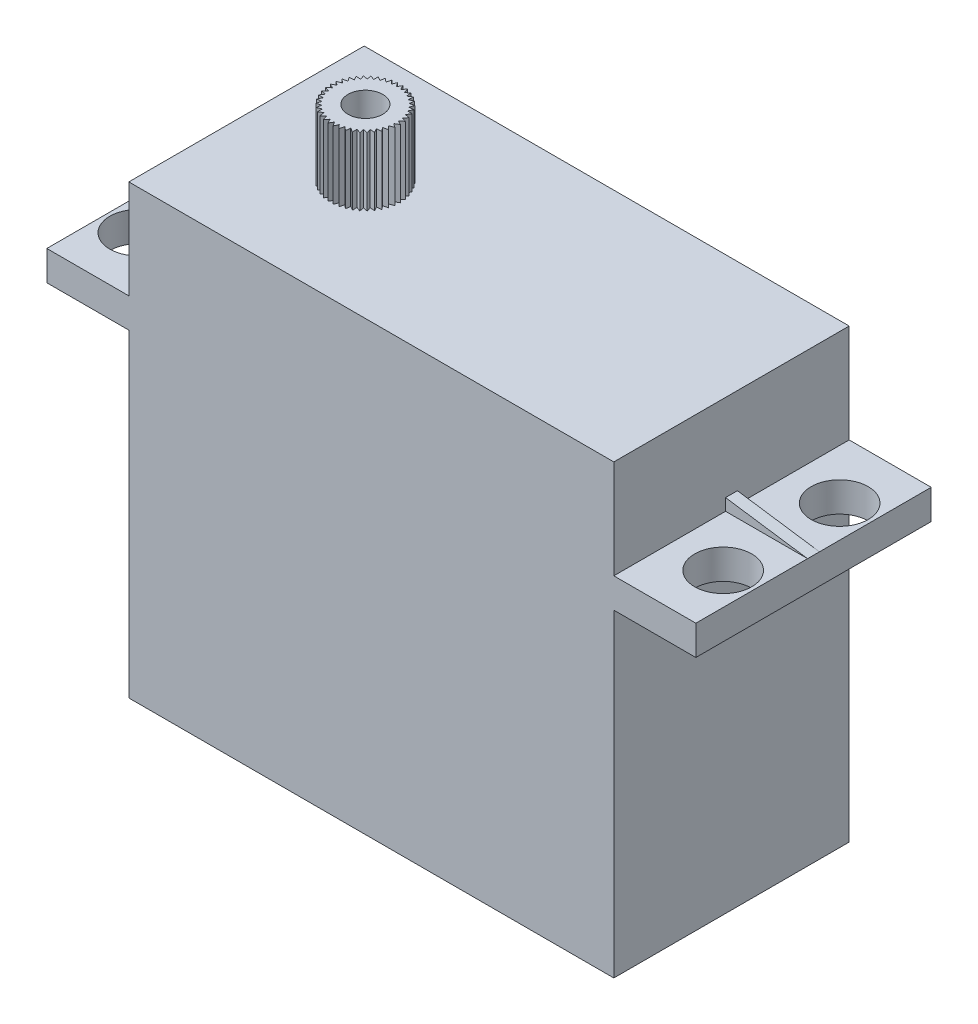
SolidWorks part; units mm, degrees
ref_plane "Front Plane" through (0, 0, 0) normal (0, 0, 1) x (1, 0, 0)
ref_plane "Top Plane" through (0, 0, 0) normal (0, 1, 0) x (1, 0, 0)
ref_plane "Right Plane" through (0, 0, 0) normal (1, 0, 0) x (0, 0, -1)
sketch "Sketch1" plane through (0, 0, 0) normal (0, 1, 0) x (1, 0, 0)
  line L1 (-27.3, -9.9) -> (27.3, -9.9)
  line L2 (-27.3, -9.9) -> (-27.3, 9.9)
  line L3 (-27.3, 9.9) -> (27.3, 9.9)
  line L4 (27.3, -9.9) -> (27.3, 9.9)
  line L5 (-27.3, -9.9) -> (27.3, 9.9) construction
  line L6 (-27.3, 9.9) -> (27.3, -9.9) construction
  point P0 (0, 0)
  dimension "D1" = 54.6
  dimension "D2" = 19.8
extrude "Full Block" add sketch "Sketch1" along normal blind 37.6
sketch "Sketch2" plane through (0, 0, 9.9) normal (0, 0, 1) x (1, 0, 0)
  line L0 (0, 0) -> (0, 37.6) construction
  line L1 (-27.3, 0) -> (27.3, 0) construction
  line L2 (-27.3, 37.6) -> (27.3, 37.6) construction
  line L4 (-20.4, 0) -> (-20.4, 37.6)
  line L5 (-20.4, 26.8) -> (-27.3, 26.8)
  line L6 (-27.3, 37.6) -> (-27.3, 0) construction
  line L7 (-27.3, 29.3) -> (-20.4, 29.3)
  line L8 (27.3, 29.3) -> (20.4, 29.3)
  line L9 (20.4, 26.8) -> (27.3, 26.8)
  line L10 (20.4, 0) -> (20.4, 37.6)
  dimension "D1" = 20.4
  dimension "D2" = 26.8
  dimension "D3" = 2.5
extrude "Tab cut" cut sketch "Sketch2" against normal up to next
sketch "Sketch5" plane through (0, 29.3, 0) normal (0, 1, 0) x (1, 0, 0)
  line L0 (-20.4, 0) -> (-27.3, 0) construction
  line L1 (-20.4, 9.9) -> (-20.4, -9.9) construction
  line L2 (-27.3, 9.9) -> (-27.3, -9.9) construction
  circle A0 centre (-24.6, 4.9) radius 2.4
  circle A1 centre (-24.6, -4.9) radius 2.4
  dimension "D3" = 4.8
  dimension "D1" = 4.9
  dimension "D2" = 4.2
extrude "Tab holes (1side)" cut sketch "Sketch5" against normal up to next
mirror "Tab holes mirror" about plane through (0, 0, 0) normal (1, 0, 0) of "Tab holes (1side)"
sketch "Sketch6" plane through (0, 29.3, 0) normal (0, 1, 0) x (1, 0, 0)
  line L0 (-20.4, 0) -> (-27.3, 0) construction
  line L1 (-20.4, 9.9) -> (-20.4, -9.9) construction
  line L2 (-27.3, 9.9) -> (-27.3, -9.9) construction
  line L4 (-27.3, -0.5) -> (-20.4, -0.5)
  line L5 (-27.3, -0.5) -> (-27.3, 0.5)
  line L6 (-27.3, 0.5) -> (-20.4, 0.5)
  line L7 (-20.4, -0.5) -> (-20.4, 0.5)
  line L8 (-27.3, -0.5) -> (-20.4, 0.5) construction
  line L9 (-27.3, 0.5) -> (-20.4, -0.5) construction
  point P6 (-23.85, 0)
  dimension "D1" = 1
extrude "Tab Fin Chunk" add sketch "Sketch6" along normal blind 1
sketch "Sketch7" plane through (0, 0, 0.5) normal (0, 0, 1) x (1, 0, 0)
  line L0 (-27.3, 29.3) -> (-20.4, 30.3)
  line L1 (-20.4, 30.3) -> (-27.3, 30.3)
  line L2 (-27.3, 30.3) -> (-27.3, 29.3)
extrude "Tab Fin Angle Cut" cut sketch "Sketch7" against normal up to next
mirror "Tab Fin Mirror" about plane through (0, 0, 0) normal (1, 0, 0) of "Tab Fin Angle Cut", "Tab Fin Chunk"
sketch "Sketch8" plane through (0, 37.6, 0) normal (0, 1, 0) x (1, 0, 0)
  line L0 (-20.4, 0) -> (0, 0) construction
  line L1 (-20.4, 9.9) -> (-20.4, -9.9) construction
  line L2 (-12.9919, 0.2054) -> (-13.35, 0)
  line L3 (-13.35, 0) -> (-12.9936, -0.1817)
  line L4 (-12.9323, 0.5894) -> (-13.3171, 0.4397)
  line L5 (-13.3171, 0.4397) -> (-12.9918, 0.2069)
  line L6 (-12.8162, 0.9602) -> (-13.2189, 0.8695)
  line L7 (-13.2189, 0.8695) -> (-12.932, 0.5909)
  line L8 (-12.6461, 1.3096) -> (-13.0579, 1.28)
  line L9 (-13.0579, 1.28) -> (-12.8156, 0.9616)
  line L10 (-12.4258, 1.6298) -> (-12.8374, 1.6618)
  line L11 (-12.8374, 1.6618) -> (-12.6453, 1.3109)
  line L12 (-12.1603, 1.9135) -> (-12.5625, 2.0065)
  line L13 (-12.5625, 2.0065) -> (-12.4249, 1.6309)
  line L14 (-11.8554, 2.1545) -> (-12.2393, 2.3064)
  line L15 (-12.2393, 2.3064) -> (-12.1592, 1.9145)
  line L16 (-11.5181, 2.3473) -> (-11.875, 2.5548)
  line L17 (-11.875, 2.5548) -> (-11.8542, 2.1553)
  line L18 (-11.1557, 2.4877) -> (-11.4778, 2.7461)
  line L19 (-11.4778, 2.7461) -> (-11.5167, 2.348)
  line L20 (-10.7765, 2.5726) -> (-11.0564, 2.876)
  line L21 (-11.0564, 2.876) -> (-11.1543, 2.4882)
  line L22 (-10.3889, 2.6) -> (-10.6205, 2.9418)
  line L23 (-10.6205, 2.9418) -> (-10.775, 2.5728)
  line L24 (-10.0015, 2.5693) -> (-10.1795, 2.9418)
  line L25 (-10.1795, 2.9418) -> (-10.3874, 2.6)
  line L26 (-9.623, 2.4812) -> (-9.7436, 2.876)
  line L27 (-9.7436, 2.876) -> (-10, 2.569)
  line L28 (-9.2619, 2.3377) -> (-9.3222, 2.7461)
  line L29 (-9.3222, 2.7461) -> (-9.6216, 2.4807)
  line L30 (-8.9262, 2.1419) -> (-8.925, 2.5548)
  line L31 (-8.925, 2.5548) -> (-9.2605, 2.337)
  line L32 (-8.6234, 1.8983) -> (-8.5607, 2.3064)
  line L33 (-8.5607, 2.3064) -> (-8.9249, 2.1411)
  line L34 (-8.3603, 1.6124) -> (-8.2375, 2.0065)
  line L35 (-8.2375, 2.0065) -> (-8.6223, 1.8973)
  line L36 (-8.1428, 1.2903) -> (-7.9626, 1.6618)
  line L37 (-7.9626, 1.6618) -> (-8.3594, 1.6112)
  line L38 (-7.9757, 0.9395) -> (-7.7421, 1.28)
  line L39 (-7.7421, 1.28) -> (-8.142, 1.289)
  line L40 (-7.8627, 0.5677) -> (-7.5811, 0.8695)
  line L41 (-7.5811, 0.8695) -> (-7.9751, 0.9381)
  line L42 (-7.8065, 0.1832) -> (-7.4829, 0.4397)
  line L43 (-7.4829, 0.4397) -> (-7.8624, 0.5662)
  line L44 (-7.8081, -0.2054) -> (-7.45, 0)
  line L45 (-7.45, 0) -> (-7.8064, 0.1817)
  line L46 (-7.8677, -0.5894) -> (-7.4829, -0.4397)
  line L47 (-7.4829, -0.4397) -> (-7.8082, -0.2069)
  line L48 (-7.9838, -0.9602) -> (-7.5811, -0.8695)
  line L49 (-7.5811, -0.8695) -> (-7.868, -0.5909)
  line L50 (-8.1539, -1.3096) -> (-7.7421, -1.28)
  line L51 (-7.7421, -1.28) -> (-7.9844, -0.9616)
  line L52 (-8.3742, -1.6298) -> (-7.9626, -1.6618)
  line L53 (-7.9626, -1.6618) -> (-8.1547, -1.3109)
  line L54 (-8.6397, -1.9135) -> (-8.2375, -2.0065)
  line L55 (-8.2375, -2.0065) -> (-8.3751, -1.6309)
  line L56 (-8.9446, -2.1545) -> (-8.5607, -2.3064)
  line L57 (-8.5607, -2.3064) -> (-8.6408, -1.9145)
  line L58 (-9.2819, -2.3473) -> (-8.925, -2.5548)
  line L59 (-8.925, -2.5548) -> (-8.9458, -2.1553)
  line L60 (-9.6443, -2.4877) -> (-9.3222, -2.7461)
  line L61 (-9.3222, -2.7461) -> (-9.2833, -2.348)
  line L62 (-10.0235, -2.5726) -> (-9.7436, -2.876)
  line L63 (-9.7436, -2.876) -> (-9.6457, -2.4882)
  line L64 (-10.4111, -2.6) -> (-10.1795, -2.9418)
  line L65 (-10.1795, -2.9418) -> (-10.025, -2.5728)
  line L66 (-10.7985, -2.5693) -> (-10.6205, -2.9418)
  line L67 (-10.6205, -2.9418) -> (-10.4126, -2.6)
  line L68 (-11.177, -2.4812) -> (-11.0564, -2.876)
  line L69 (-11.0564, -2.876) -> (-10.8, -2.569)
  line L70 (-11.5381, -2.3377) -> (-11.4778, -2.7461)
  line L71 (-11.4778, -2.7461) -> (-11.1784, -2.4807)
  line L72 (-11.8738, -2.1419) -> (-11.875, -2.5548)
  line L73 (-11.875, -2.5548) -> (-11.5395, -2.337)
  line L74 (-12.1766, -1.8983) -> (-12.2393, -2.3064)
  line L75 (-12.2393, -2.3064) -> (-11.8751, -2.1411)
  line L76 (-12.4397, -1.6124) -> (-12.5625, -2.0065)
  line L77 (-12.5625, -2.0065) -> (-12.1777, -1.8973)
  line L78 (-12.6572, -1.2903) -> (-12.8374, -1.6618)
  line L79 (-12.8374, -1.6618) -> (-12.4406, -1.6112)
  line L80 (-12.8243, -0.9395) -> (-13.0579, -1.28)
  line L81 (-13.0579, -1.28) -> (-12.658, -1.289)
  line L82 (-12.9373, -0.5677) -> (-13.2189, -0.8695)
  line L83 (-13.2189, -0.8695) -> (-12.8249, -0.9381)
  line L84 (-12.9935, -0.1832) -> (-13.3171, -0.4397)
  line L85 (-13.3171, -0.4397) -> (-12.9376, -0.5662)
  line L86 (-10.4, 0) -> (-12.9919, 0.2054) construction
  circle A0 centre (-10.4, 0) radius 2.95
  arc A1 (-12.8249, -0.9381) -> (-12.8243, -0.9395) centre (-10.4, 0) ccw
  arc A2 (-12.9376, -0.5662) -> (-12.9373, -0.5677) centre (-10.4, 0) ccw
  arc A3 (-13, 0) -> (-12.9935, -0.1832) centre (-10.4, 0) ccw
  arc A4 (-12.9918, 0.2069) -> (-12.9919, 0.2054) centre (-10.4, 0) ccw
  arc A5 (-12.932, 0.5909) -> (-12.9323, 0.5894) centre (-10.4, 0) ccw
  arc A6 (-12.8156, 0.9616) -> (-12.8162, 0.9602) centre (-10.4, 0) ccw
  arc A7 (-12.6453, 1.3109) -> (-12.6461, 1.3096) centre (-10.4, 0) ccw
  arc A8 (-12.4249, 1.6309) -> (-12.4258, 1.6298) centre (-10.4, 0) ccw
  arc A9 (-12.1592, 1.9145) -> (-12.1603, 1.9135) centre (-10.4, 0) ccw
  arc A10 (-11.8542, 2.1553) -> (-11.8554, 2.1545) centre (-10.4, 0) ccw
  arc A11 (-11.5167, 2.348) -> (-11.5181, 2.3473) centre (-10.4, 0) ccw
  arc A12 (-11.1543, 2.4882) -> (-11.1557, 2.4877) centre (-10.4, 0) ccw
  arc A13 (-10.775, 2.5728) -> (-10.7765, 2.5726) centre (-10.4, 0) ccw
  arc A14 (-10.3874, 2.6) -> (-10.3889, 2.6) centre (-10.4, 0) ccw
  arc A15 (-10, 2.569) -> (-10.0015, 2.5693) centre (-10.4, 0) ccw
  arc A16 (-9.6216, 2.4807) -> (-9.623, 2.4812) centre (-10.4, 0) ccw
  arc A17 (-9.2605, 2.337) -> (-9.2619, 2.3377) centre (-10.4, 0) ccw
  arc A18 (-8.9249, 2.1411) -> (-8.9262, 2.1419) centre (-10.4, 0) ccw
  arc A19 (-8.6223, 1.8973) -> (-8.6234, 1.8983) centre (-10.4, 0) ccw
  arc A20 (-8.3594, 1.6112) -> (-8.3603, 1.6124) centre (-10.4, 0) ccw
  arc A21 (-8.142, 1.289) -> (-8.1428, 1.2903) centre (-10.4, 0) ccw
  arc A22 (-7.9751, 0.9381) -> (-7.9757, 0.9395) centre (-10.4, 0) ccw
  arc A23 (-7.8624, 0.5662) -> (-7.8627, 0.5677) centre (-10.4, 0) ccw
  arc A24 (-7.8, 0) -> (-7.8065, 0.1832) centre (-10.4, 0) ccw
  arc A25 (-7.8082, -0.2069) -> (-7.8081, -0.2054) centre (-10.4, 0) ccw
  arc A26 (-7.868, -0.5909) -> (-7.8677, -0.5894) centre (-10.4, 0) ccw
  arc A27 (-7.9844, -0.9616) -> (-7.9838, -0.9602) centre (-10.4, 0) ccw
  arc A28 (-8.1547, -1.3109) -> (-8.1539, -1.3096) centre (-10.4, 0) ccw
  arc A29 (-8.3751, -1.6309) -> (-8.3742, -1.6298) centre (-10.4, 0) ccw
  arc A30 (-8.6408, -1.9145) -> (-8.6397, -1.9135) centre (-10.4, 0) ccw
  arc A31 (-8.9458, -2.1553) -> (-8.9446, -2.1545) centre (-10.4, 0) ccw
  arc A32 (-9.2833, -2.348) -> (-9.2819, -2.3473) centre (-10.4, 0) ccw
  arc A33 (-9.6457, -2.4882) -> (-9.6443, -2.4877) centre (-10.4, 0) ccw
  arc A34 (-10.025, -2.5728) -> (-10.0235, -2.5726) centre (-10.4, 0) ccw
  arc A35 (-10.4126, -2.6) -> (-10.4111, -2.6) centre (-10.4, 0) ccw
  arc A36 (-10.8, -2.569) -> (-10.7985, -2.5693) centre (-10.4, 0) ccw
  arc A37 (-11.1784, -2.4807) -> (-11.177, -2.4812) centre (-10.4, 0) ccw
  arc A38 (-11.5395, -2.337) -> (-11.5381, -2.3377) centre (-10.4, 0) ccw
  arc A39 (-11.8751, -2.1411) -> (-11.8738, -2.1419) centre (-10.4, 0) ccw
  arc A40 (-12.4406, -1.6112) -> (-12.4397, -1.6124) centre (-10.4, 0) ccw
  arc A41 (-12.658, -1.289) -> (-12.6572, -1.2903) centre (-10.4, 0) ccw
  arc A42 (-12.1777, -1.8973) -> (-12.1766, -1.8983) centre (-10.4, 0) ccw
  circle A43 centre (-10.4, 0) radius 1.46
  dimension "D1" = 5.9
  dimension "D3" = 2.92
  dimension "D2" = 10
  dimension "D4" = 0.4
  dimension "D5" = 0.4128
  dimension "D6" = 42
  dimension "D7" = 2.6
extrude "Rotor" add sketch "Sketch8" along normal blind 5.7
